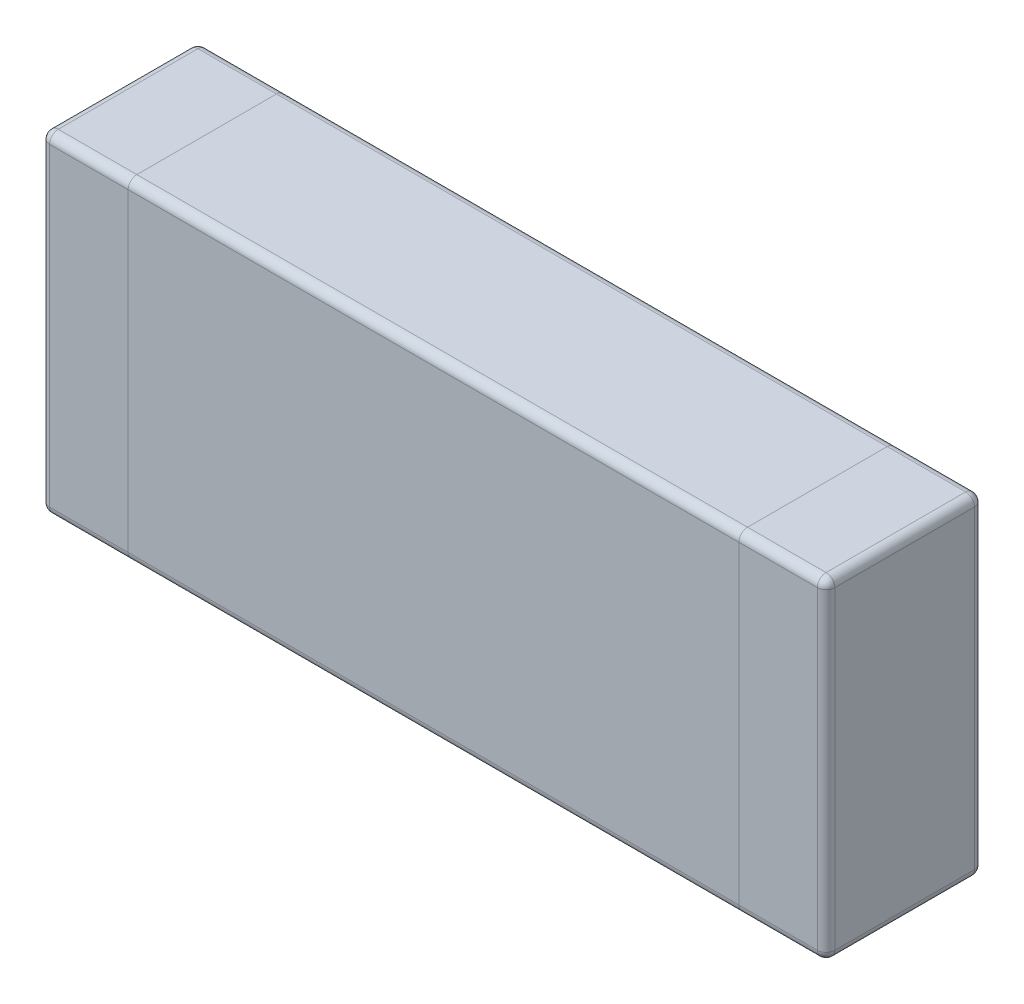
SolidWorks part; units mm, degrees
ref_plane "Front Plane" through (0, 0, 0) normal (0, 0, 1) x (1, 0, 0)
ref_plane "Top Plane" through (0, 0, 0) normal (0, 1, 0) x (1, 0, 0)
ref_plane "Right Plane" through (0, 0, 0) normal (1, 0, 0) x (0, 0, -1)
sketch "Sketch1" plane through (0, 0, 0) normal (0, 1, 0) x (1, 0, 0)
  line L1 (-2.25, -0.45) -> (2.25, -0.45)
  line L2 (-2.25, -0.45) -> (-2.25, 0.45)
  line L3 (-2.25, 0.45) -> (2.25, 0.45)
  line L4 (2.25, -0.45) -> (2.25, 0.45)
  line L5 (-2.25, -0.45) -> (2.25, 0.45) construction
  line L6 (-2.25, 0.45) -> (2.25, -0.45) construction
  point P0 (0, 0)
  dimension "D1" = 4.5
  dimension "D2" = 0.9
extrude "Extrude1" add sketch "Sketch1" along normal blind 1.9
fillet "Fillet1" radius 0.05 12 edges at (2.25, 0.95, -0.45) (-2.25, 0.95, -0.45) (-2.25, 0.95, 0.45) (2.25, 0.95, 0.45) (0, 1.9, 0.45) (-2.25, 1.9, 0) (0, 1.9, -0.45) (2.25, 1.9, 0) (0, 0, -0.45) (-2.25, 0, 0) (0, 0, 0.45) (2.25, 0, 0)
sketch "Sketch2" plane through (0, 0, 0) normal (0, 1, 0) x (1, 0, 0)
  line L0 (-2.2, 0.45) -> (2.2, 0.45) construction
  line L1 (-1.75, -0.45) -> (1.75, -0.45)
  line L2 (-1.75, -0.45) -> (-1.75, 0.45)
  line L3 (-1.75, 0.45) -> (1.75, 0.45)
  line L4 (1.75, -0.45) -> (1.75, 0.45)
  line L5 (2.2, -0.45) -> (-2.2, -0.45) construction
  line L6 (0, 0.4) -> (0, -0.6635) construction
  line L7 (2.2, 0.4) -> (-2.2, 0.4) construction
  line L9 (-2.25, -0.4) -> (-2.25, 0.4) construction
  dimension "D1" = 0.5
split line "Split Line3"
